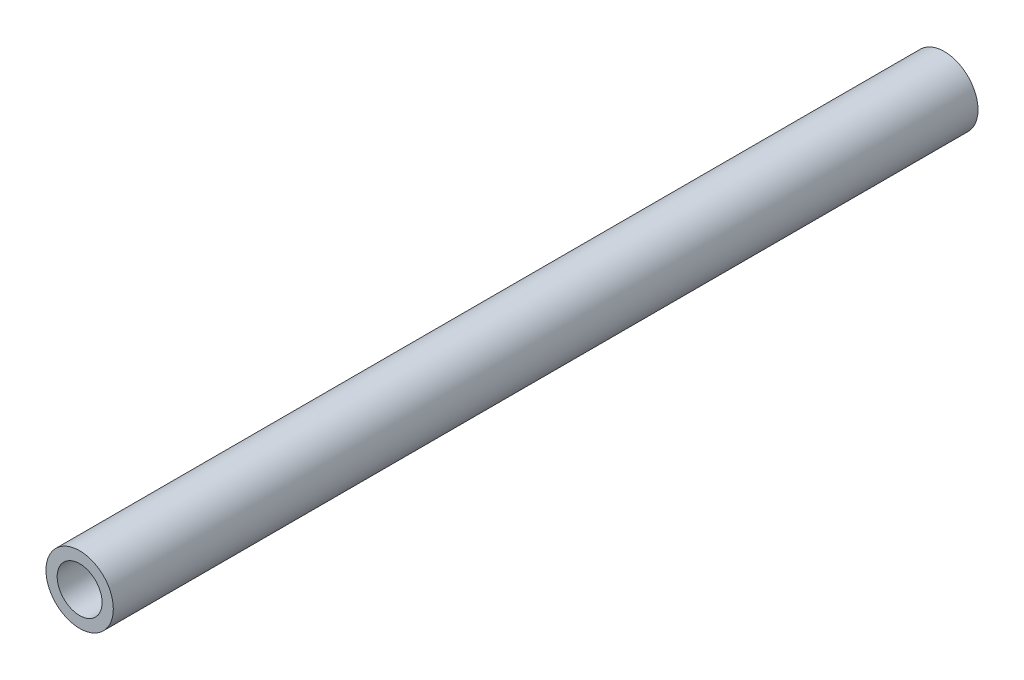
SolidWorks part; units mm, degrees
material "Rubber"
ref_plane "Front Plane" through (0, 0, 0) normal (0, 0, 1) x (1, 0, 0)
ref_plane "Top Plane" through (0, 0, 0) normal (0, 1, 0) x (1, 0, 0)
ref_plane "Right Plane" through (0, 0, 0) normal (1, 0, 0) x (0, 0, -1)
sketch "Sketch1" plane through (0, 0, 0) normal (0, 0, 1) x (1, 0, 0)
  circle A0 centre (0, 0) radius 19.05
extrude "Boss-Extrude1" add sketch "Sketch1" along normal blind 488.95
sketch "Sketch2" plane through (0, 0, 488.95) normal (0, 0, 1) x (1, 0, 0)
  circle A0 centre (0, 0) radius 12.7
extrude "Cut-Extrude1" cut sketch "Sketch2" against normal blind 539.75
